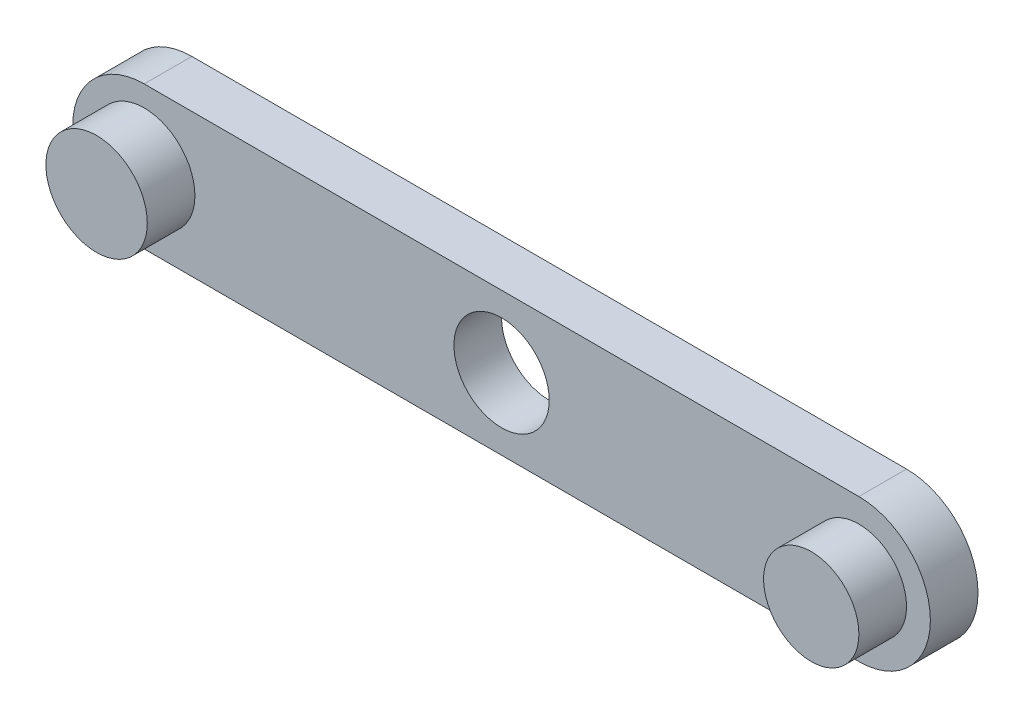
SolidWorks part; units mm, degrees
ref_plane "Front Plane" through (0, 0, 0) normal (0, 0, 1) x (1, 0, 0)
ref_plane "Top Plane" through (0, 0, 0) normal (0, 1, 0) x (1, 0, 0)
ref_plane "Right Plane" through (0, 0, 0) normal (1, 0, 0) x (0, 0, -1)
sketch "Sketch1" plane through (0, 0, 0) normal (0, 0, 1) x (1, 0, 0)
  line L0 (0, 0) -> (150, 0) construction
  line L1 (0, 15) -> (150, 15)
  line L2 (0, -15) -> (150, -15)
  arc A0 (0, 15) -> (0, -15) centre (0, 0) ccw
  arc A1 (150, -15) -> (150, 15) centre (150, 0) ccw
  circle A2 centre (75, 0) radius 10
  point P3 (75, 0)
  dimension "D1" = 150
  dimension "D2" = 30
extrude "Boss-Extrude1" add sketch "Sketch1" along normal blind 10
sketch "Sketch2" plane through (0, 0, 10) normal (0, 0, 1) x (1, 0, 0)
  circle A0 centre (0, 0) radius 10.6386
  circle A1 centre (150, 0) radius 10
extrude "Boss-Extrude2" add sketch "Sketch2" along normal blind 10
